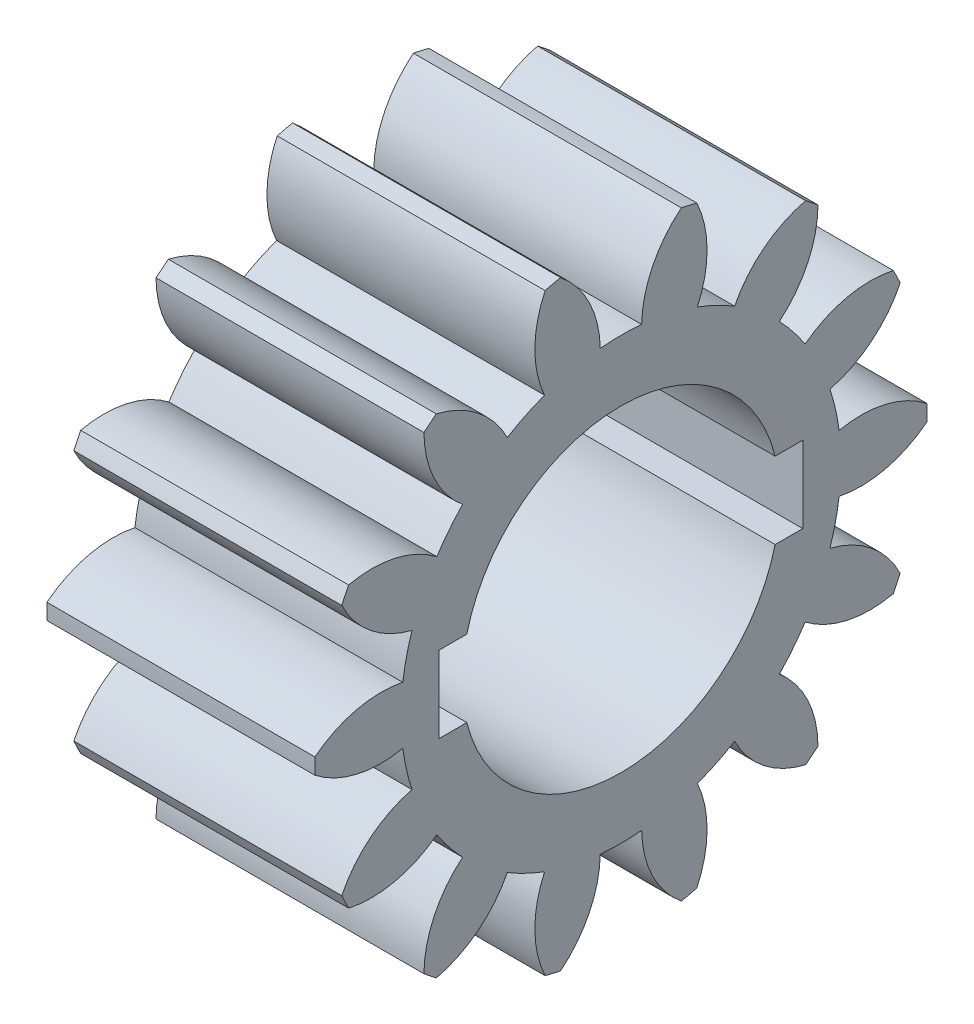
SolidWorks part; units mm, degrees
ref_plane "Plane1" through (0, 0, 0) normal (0, 0, 1) x (1, 0, 0)
ref_plane "Plane2" through (0, 0, 0) normal (0, 1, 0) x (1, 0, 0)
ref_plane "Plane3" through (0, 0, 0) normal (1, 0, 0) x (0, 0, -1)
sketch "HoldingSke" plane through (0, 0, 0) normal (0, 1, 0) x (1, 0, 0)
  line L0 (0, 0) -> (0.9703, -0.2419)
  line L1 (-15, 0) -> (100, 0) construction
  line L2 (0, 0) -> (-2.1039, 2.3779)
  line L3 (0, 0) -> (-11.863, 4.5341)
  line L4 (0, 0) -> (8.3795, 2.0892)
  line L5 (0, 0) -> (-46.8476, -17.4728)
  line L6 (0, 0) -> (-5.8027, -3.9151)
  line L7 (-2.1039, 2.3779) -> (8.6586, 51.2059)
  line L8 (-76.2, 54.61) -> (-75.3, 54.61)
  line L9 (-71.009, 38.7566) -> (-53.1078, 45.2721)
  line L10 (-76.2, 71.12) -> (104.1128, 71.12)
  line L11 (0, 0) -> (-7, 0)
  line L12 (-76.2, 101.6) -> (-76.162, 101.6)
  line L13 (24.9733, 27.94) -> (52.9518, 28.4284)
  line L14 (24.9733, 27.94) -> (24.9743, 27.94)
  line L15 (24.9733, 27.94) -> (100.4006, 29.5858)
  line L16 (-63.627, -1) -> (-12.827, -1)
  circle A0 centre (0, 0) radius 2.5
  circle A1 centre (0, 0) radius 5.749
  circle A2 centre (0, 0) radius 37.5
  circle A3 centre (0, 0) radius 2.5
  dimension "MHD" = 11.498
  dimension "Hub_dia" = 75
  dimension "Bore" = 5
  dimension "MBD" = 5
  dimension "Num_teeth" = 14
  dimension "Pitch" = 1
  dimension "Overall_len" = 50
  dimension "Show_teeth" = 14
  dimension "Thickness" = 7
  dimension "OAL" = 50.0001
  dimension "T_dim" = 0.9
  dimension "Ap" = 20
  dimension "H" = 19.05
  dimension "Pitch_radius" = 180.3128
  dimension "Width" = 7
  dimension "Backlash" = 0.038
  dimension "Addendum_fac" = 1
  dimension "Dedendum_fac" = 1.25
  dimension "Clearance_fac" = 0.25
  dimension "Dedendum_add" = 0.001
  dimension "Module" = 1
sketch "BasProSke" plane through (0, 0, 0) normal (0, 1, 0) x (1, 0, 0)
  line L0 (-10, 0) -> (60, 0) construction
  line L1 (0, 0) -> (0, 8)
  line L2 (0, 0) -> (7, 0)
  line L3 (7, 0) -> (7, 8)
  line L4 (7, 8) -> (0, 8)
  dimension "Thickness" = 7
  dimension "Diameter" = 16
revolve "Base-Revolve" add sketch "BasProSke" angle 360 about L0
sketch "TooCutSke" plane through (0, 0, 0) normal (1, 0, 0) x (0, 0, -1)
  line L1 (0, 0) -> (0, 107) construction
  line L2 (0, 0) -> (-0.8502, 6.9482) construction
  line L3 (0, 0) -> (-3.0989, 13.5772) construction
  line L4 (-0.8502, 6.9482) -> (-1.5494, 6.7886) construction
  arc A0 (0.5404, 5.7235) -> (-0.5404, 5.7235) centre (0, 0) ccw
  arc A1 (1.6036, 7.8636) -> (-1.6036, 7.8636) centre (0, 0) ccw
  circle A2 centre (0, 0) radius 7 construction
  circle A3 centre (0, 0) radius 6.5778 construction
  arc A4 (-0.5404, 5.7235) -> (-1.6036, 7.8636) centre (-3.3398, 5.6669) ccw
  arc A5 (1.6036, 7.8636) -> (0.5404, 5.7235) centre (3.3398, 5.6669) ccw
  dimension "Root_dia" = 11.498
  dimension "Overcut_dia" = 16.0508
  dimension "Pitch_dia" = 14
  dimension "Base_dia" = 13.1557
  dimension "Flank_rad" = 2.8
  dimension "Half_ang" = 12.857
  dimension "Half_CT" = 0.7173
extrude "ToothCut" cut sketch "TooCutSke" along normal through all
fillet "Breaks" [suppressed] radius 0.02
fillet "RootFillets" [suppressed] radius 0.251
pattern_circular "TeethCuts" count 14 every 25.714 about axis through (-10, 0, 0) along (1, 0, 0) of "ToothCut", "RootFillets", "Breaks"
sketch "HubNeaOneSke" plane through (0, 0, 0) normal (-1, 0, 0) x (0, 0, 1)
  circle A0 centre (0, 0) radius 5.749
  dimension "Diameter" = 11.498
extrude "HubNearOne" [suppressed] add sketch "HubNeaOneSke" along normal blind 43.0001
sketch "HubNeaBotSke" plane through (0, 0, 0) normal (-1, 0, 0) x (0, 0, 1)
  circle A0 centre (0, 0) radius 5.749
  dimension "Diameter" = 11.498
extrude "HubNearBoth" [suppressed] add sketch "HubNeaBotSke" along normal blind 21.5
ref_plane "FarPln" through (7, 0, 0) normal (1, 0, 0) x (0, 0, -1)
sketch "HubFarSke" plane through (7, 0, 0) normal (1, 0, 0) x (0, 0, -1)
  circle A0 centre (0, 0) radius 5.749
  dimension "Diameter" = 11.498
extrude "HubFar" [suppressed] add sketch "HubFarSke" along normal blind 21.5
sketch "BorSke" plane through (0, 0, 0) normal (1, 0, 0) x (0, 0, -1)
  circle A0 centre (0, 0) radius 2.5
  dimension "Diameter" = 5
extrude "Bore" cut sketch "BorSke" along normal mid plane 100.0001
sketch "KeySke" plane through (0, 0, 0) normal (1, 0, 0) x (0, 0, -1)
  line L0 (-1, 0) -> (-1, 3.4)
  line L1 (-1, 3.4) -> (1, 3.4)
  line L2 (1, 3.4) -> (1, 0)
  line L3 (0, 0) -> (0, 34) construction
  line L4 (-1, 0) -> (1, 0)
  dimension "Offset" = 3.4
  dimension "Width" = 2
extrude "Keyway" [suppressed] cut sketch "KeySke" along normal mid plane 100.0001
pattern_circular "Keyway2" [suppressed] count 2 every 90 about axis through (-10, 0, 0) along (1, 0, 0)
sketch "Sketch1" plane through (7, 0, 0) normal (1, 0, 0) x (0, 0, -1)
  line L12 (4.75, 1.5) -> (4.75, -1) construction
  line L14 (-4.75, 1.5) -> (-4.75, -1.5) construction
  line L15 (3.873, 1) -> (4.75, 1)
  line L16 (-4.75, 1) -> (-3.873, 1)
  line L17 (-4.75, 1) -> (-4.75, -1)
  line L18 (-4.75, -1) -> (-3.873, -1)
  line L20 (4.75, 1) -> (4.75, -1)
  line L21 (-4.75, 1) -> (4.75, -1) construction
  line L22 (-4.75, -1) -> (4.75, 1) construction
  line L23 (3.873, -1) -> (4.75, -1)
  arc A2 (-3.873, -1) -> (3.873, -1) centre (0, 0) ccw
  arc A3 (3.873, 1) -> (-3.873, 1) centre (0, 0) ccw
  dimension "D1" = 8
  dimension "D2" = 3
  dimension "D4" = 2
extrude "Cut-Extrude2" cut sketch "Sketch1" against normal blind 10
sketch "Sketch2" plane through (7, 0, 0) normal (1, 0, 0) x (0, 0, -1)
  circle A0 centre (0, 0) radius 4.15
extrude "Cut-Extrude3" cut sketch "Sketch2" against normal through all
equation "' \"Module@HoldingSke\" = 6.35"
equation "' \"Num_teeth@HoldingSke\" = 12"
equation "' \"Ap@HoldingSke\" =  20"
equation "' \"Ap@HoldingSke\" = 20"
equation "' \"Width@HoldingSke\" = 0.5 * 25.4"
equation "' \"Hub_dia@HoldingSke\"= 1 * 25.4"
equation "' \"Hub_dia@HoldingSke\" = 1 * 25.4"
equation "' \"Overall_len@HoldingSke\" = 1.0 * 25.4"
equation "' \"Bore@HoldingSke\" = 0.75 * 25.4"
equation "' \"T_dim@HoldingSke\" = 0.1 * 25.4"
equation "' \"Width@KeySke\" = 0.25 * 25.4"
equation "' \"Show_teeth@HoldingSke\" = 13"
equation "' \"Backlash@HoldingSke\" = 0.009 * 25.4"
equation "' \"Addendum_fac@HoldingSke\" = 1.0"
equation "' \"Dedendum_fac@HoldingSke\" = 1.25"
equation "' \"Dedendum_add@HoldingSke\" = 0.00005 * 25.4"
equation "' \"Clearance_fac@HoldingSke\" = 0.25"
equation "\"Pitch@HoldingSke\" = 1 / \"Module@HoldingSke\""
equation "\"Overcut_dia@TooCutSke\" = (\"Num_teeth@HoldingSke\" + 2 * \"Addendum_fac@HoldingSke\") / \"Pitch@HoldingSke\" + 0.002 * 25.4"
equation "\"Pitch_dia@TooCutSke\" = \"Num_teeth@HoldingSke\" / \"Pitch@HoldingSke\""
equation "\"Base_dia@TooCutSke\" = \"Num_teeth@HoldingSke\" / \"Pitch@HoldingSke\" * cos((\"Ap@HoldingSke\"  * 3.14159265 / 180))"
equation "\"Root_dia@TooCutSke\" = (\"Num_teeth@HoldingSke\" + 2) / \"Pitch@HoldingSke\" - 2 * (\"Addendum_fac@HoldingSke\" + \"Dedendum_fac@HoldingSke\") / \"Pitch@HoldingSke\" - \"Dedendum_add@HoldingSke\" * 2"
equation "\"Half_ang@TooCutSke\" = 180 / \"Num_teeth@HoldingSke\""
equation "\"Half_CT@TooCutSke\" = \"Num_teeth@HoldingSke\" / \"Pitch@HoldingSke\" * sin((3.14159265 / 2 / \"Num_teeth@HoldingSke\")) / 2 - 7 * \"Backlash@HoldingSke\" / 4"
equation "\"Flank_rad@TooCutSke\" = \"Num_teeth@HoldingSke\" / \"Pitch@HoldingSke\" / 5"
equation "\"Radius@RootFillets\" = \"Clearance_fac@HoldingSke\" / \"Pitch@HoldingSke\" + \"Dedendum_add@HoldingSke\""
equation "\"Break_rad@Breaks\" = 0.02 / \"Pitch@HoldingSke\""
equation "\"Thickness@HoldingSke\" = \"Width@HoldingSke\""
equation "\"OAL@HoldingSke\" = \"Thickness@HoldingSke\""
equation "\"MHD@HoldingSke\" = (\"Num_teeth@HoldingSke\" + 2) / \"Pitch@HoldingSke\" - 2 * (\"Addendum_fac@HoldingSke\" + \"Dedendum_fac@HoldingSke\")  / \"Pitch@HoldingSke\" - \"Dedendum_add@HoldingSke\" * 2"
equation "\"MBD@HoldingSke\" = (\"Num_teeth@HoldingSke\" + 2) / \"Pitch@HoldingSke\" - 2 * (\"Addendum_fac@HoldingSke\" + \"Dedendum_fac@HoldingSke\")  / \"Pitch@HoldingSke\" - \"Dedendum_add@HoldingSke\" * 2 - 0.002 * 25.4"
equation "\"MHD@HoldingSke\" = ((sgn( \"MHD@HoldingSke\" - \"Hub_dia@HoldingSke\" )-1)*( \"MHD@HoldingSke\" - \"Hub_dia@HoldingSke\" ))/-2+ \"Hub_dia@HoldingSke\""
equation "\"MBD@HoldingSke\" = ((sgn( \"MBD@HoldingSke\" - \"Bore@HoldingSke\" )-1)*( \"MBD@HoldingSke\" - \"Bore@HoldingSke\" ))/-2+ \"Bore@HoldingSke\""
equation "\"OAL@HoldingSke\" = ((sgn( \"OAL@HoldingSke\" - \"Overall_len@HoldingSke\" )+1)*( \"OAL@HoldingSke\" - \"Overall_len@HoldingSke\" ))/2 + \"Overall_len@HoldingSke\" + 0.000002 * 25.4"
equation "\"Num_teeth@TeethCuts\" = int( \"Show_teeth@HoldingSke\" ) + 1"
equation "\"Num_teeth@TeethCuts\" = ((sgn( \"Num_teeth@TeethCuts\" - \"Num_teeth@HoldingSke\" )-1)*( \"Num_teeth@TeethCuts\" - \"Num_teeth@HoldingSke\" ))/-2+ \"Num_teeth@HoldingSke\""
equation "\"Num_teeth@TeethCuts\" = ((sgn( \"Num_teeth@TeethCuts\" - 2.0)+1)*( \"Num_teeth@TeethCuts\" - 2.0))/2 +2.0"
equation "\"Angle@TeethCuts\" = 360.0 / \"Num_teeth@HoldingSke\""
equation "\"Diameter@BasProSke\" = (\"Num_teeth@HoldingSke\" + 2 * \"Addendum_fac@HoldingSke\") / \"Pitch@HoldingSke\""
equation "\"Thickness@BasProSke\"  = \"Thickness@HoldingSke\""
equation "' \"Fillet_rad@BasProSke\" =  \"Thickness@HoldingSke\" * 0.05"
equation "' \"Fillet_rad@BasProSke\" = \"Thickness@HoldingSke\" * 0.05"
equation "\"MHD@HoldingSke\" = ((sgn( \"MHD@HoldingSke\" - \"Root_dia@TooCutSke\" )-1)*( \"MHD@HoldingSke\" - \"Root_dia@TooCutSke\" ))/-2+ \"Root_dia@TooCutSke\""
equation "\"Diameter@HubNeaOneSke\" = \"MHD@HoldingSke\""
equation "\"Length@HubNearOne\" = \"OAL@HoldingSke\" - \"Thickness@BasProSke\""
equation "\"Diameter@HubNeaBotSke\" = \"MHD@HoldingSke\""
equation "\"Length@HubNearBoth\" = ( \"OAL@HoldingSke\" - \"Thickness@BasProSke\" ) / 2.0"
equation "\"Thickness@FarPln\" = \"Thickness@BasProSke\""
equation "\"Diameter@HubFarSke\" = \"MHD@HoldingSke\""
equation "\"Length@HubFar\" = ( \"OAL@HoldingSke\" - \"Thickness@BasProSke\" ) / 2.0"
equation "\"Diameter@BorSke\" = \"MBD@HoldingSke\""
equation "\"D1@Bore\" = \"OAL@HoldingSke\" * 2.0"
equation "\"D1@Keyway\" = \"OAL@HoldingSke\" * 2.0"
equation "\"Offset@KeySke\" = \"T_dim@HoldingSke\" + \"MBD@HoldingSke\" / 2.0"
